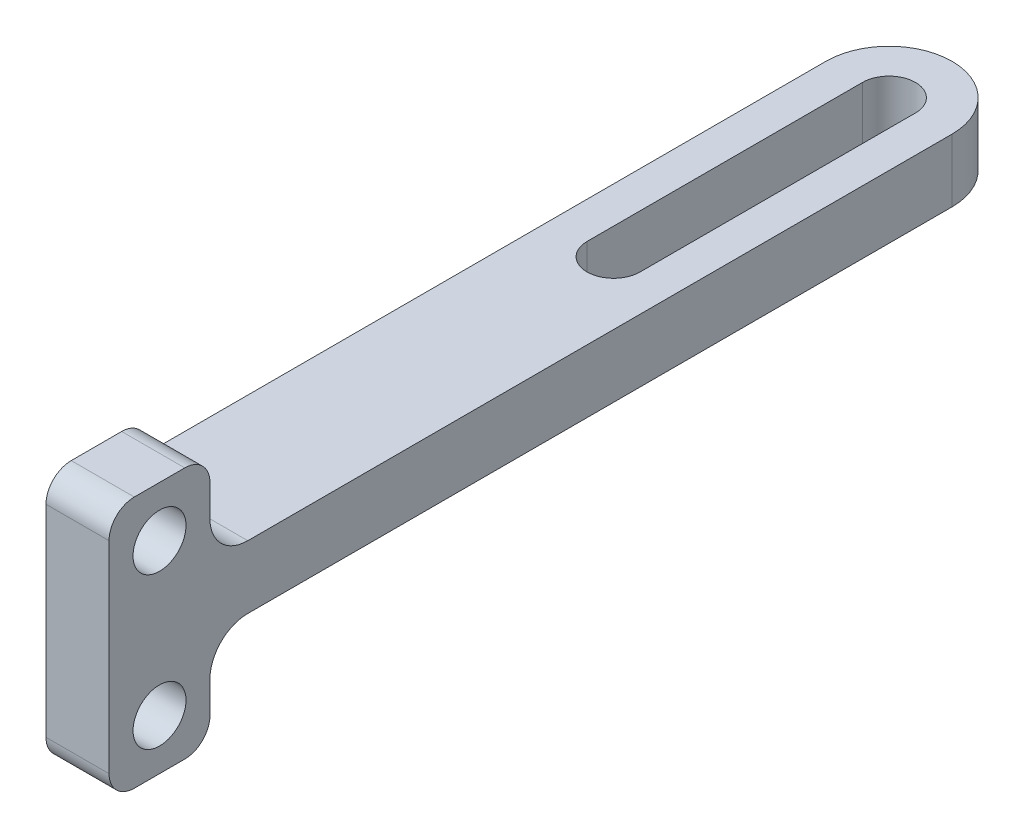
SolidWorks part; units mm, degrees
ref_plane "Front" through (0, 0, 0) normal (0, 0, 1) x (1, 0, 0)
ref_plane "Top" through (0, 0, 0) normal (0, 1, 0) x (1, 0, 0)
ref_plane "Right" through (0, 0, 0) normal (1, 0, 0) x (0, 0, -1)
sketch "Sketch1" plane through (0, 0, 0) normal (0, 1, 0) x (1, 0, 0)
  line L1 (-5, 0) -> (-5, 13.8358)
  line L6 (-5, 0) -> (-5, -45)
  line L7 (-5, -45) -> (5, -45)
  line L8 (5, -45) -> (5, 0)
  line L10 (5, 0) -> (5, 13.8358)
  line L11 (-2.1, -8) -> (-2.1, 13.8358)
  line L12 (2.1, 13.8358) -> (2.1, -8)
  arc A4 (2.1, 13.8358) -> (-2.1, 13.8358) centre (0, 13.8358) ccw
  arc A5 (-2.1, -8) -> (2.1, -8) centre (0, -8) ccw
  arc A6 (5, 13.8358) -> (-5, 13.8358) centre (0, 13.8358) ccw
extrude "Boss-Extrude1" add sketch "Sketch1" along normal blind 5
sketch "Sketch2" plane through (0, 0, 45) normal (0, 0, 1) x (1, 0, 0)
  line L1 (0, 12.5) -> (0, -7.5)
  line L6 (0, -7.5) -> (5, -7.5)
  line L12 (0, 12.5) -> (5, 12.5)
  line L13 (5, -7.5) -> (5, 12.5)
  point P4 (0, 2.5)
  point P7 (0, 2.5)
  point P9 (5, 2.5)
extrude "Boss-Extrude2" add sketch "Sketch2" along normal blind 8
sketch "Sketch3" plane through (5, 0, 0) normal (1, 0, 0) x (0, 0, -1)
  circle A0 centre (-49, 8.5) radius 2.1
  circle A1 centre (-49, -3.5) radius 2.1
extrude "Cut-Extrude1" cut sketch "Sketch3" against normal blind 8
fillet "Fillet2" radius 2 4 edges at (2.5, -7.5, 45) (2.5, -7.5, 53) (2.5, 12.5, 45) (2.5, 12.5, 53)
sketch "Sketch4" plane through (0, 0, 45) normal (0, 0, 1) x (1, 0, 0)
  line L0 (-5, 0) -> (-5, 5)
  line L3 (-5, 0) -> (0, 0)
  line L4 (0, 5) -> (0, 0)
  line L5 (-5, 5) -> (0, 5)
extrude "Cut-Extrude2" cut sketch "Sketch4" against normal blind 3
fillet "Fillet3" radius 3 3 edges at (2.5, 0, 45) (2.5, 5, 45) (-5, 2.5, 42)
